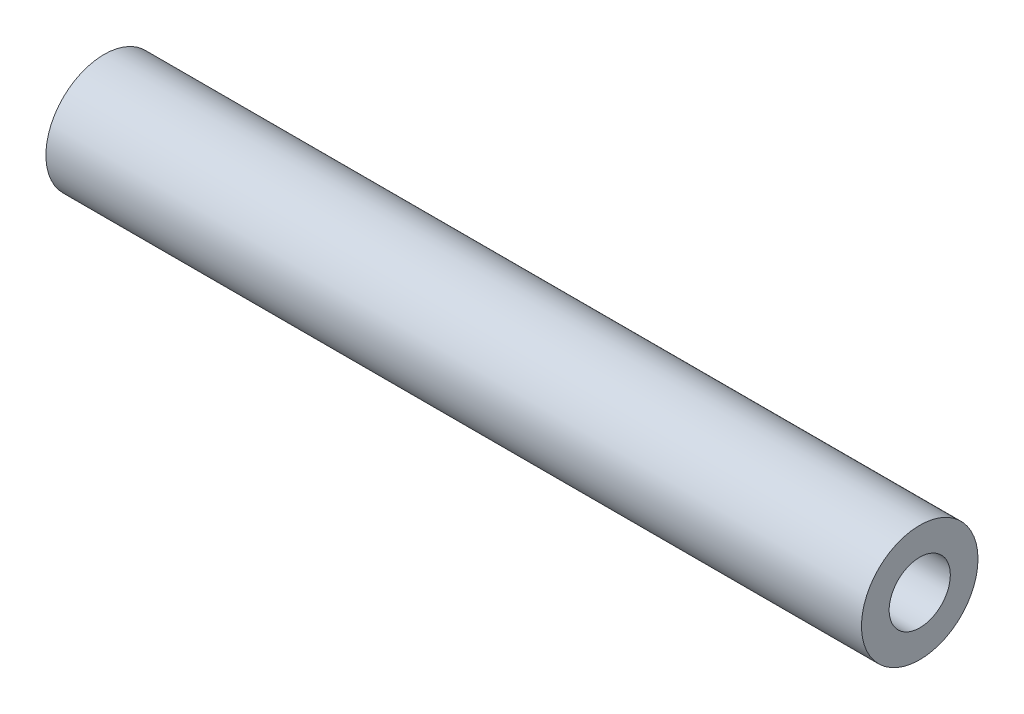
SolidWorks part; units mm, degrees
material "6061-T6 (SS)"
ref_plane "前视基准面" through (0, 0, 0) normal (0, 0, 1) x (1, 0, 0)
ref_plane "上视基准面" through (0, 0, 0) normal (0, 1, 0) x (1, 0, 0)
ref_plane "右视基准面" through (0, 0, 0) normal (1, 0, 0) x (0, 0, -1)
other "Configuration Table"
sketch "草图1" plane through (0, 0, 0) normal (1, 0, 0) x (0, 0, -1)
  circle A0 centre (0, 0) radius 2.1
  circle A1 centre (0, 0) radius 4
  dimension "D1" = 4.2
  dimension "D2" = 8
extrude "凸台-拉伸1" add sketch "草图1" along normal blind 56
